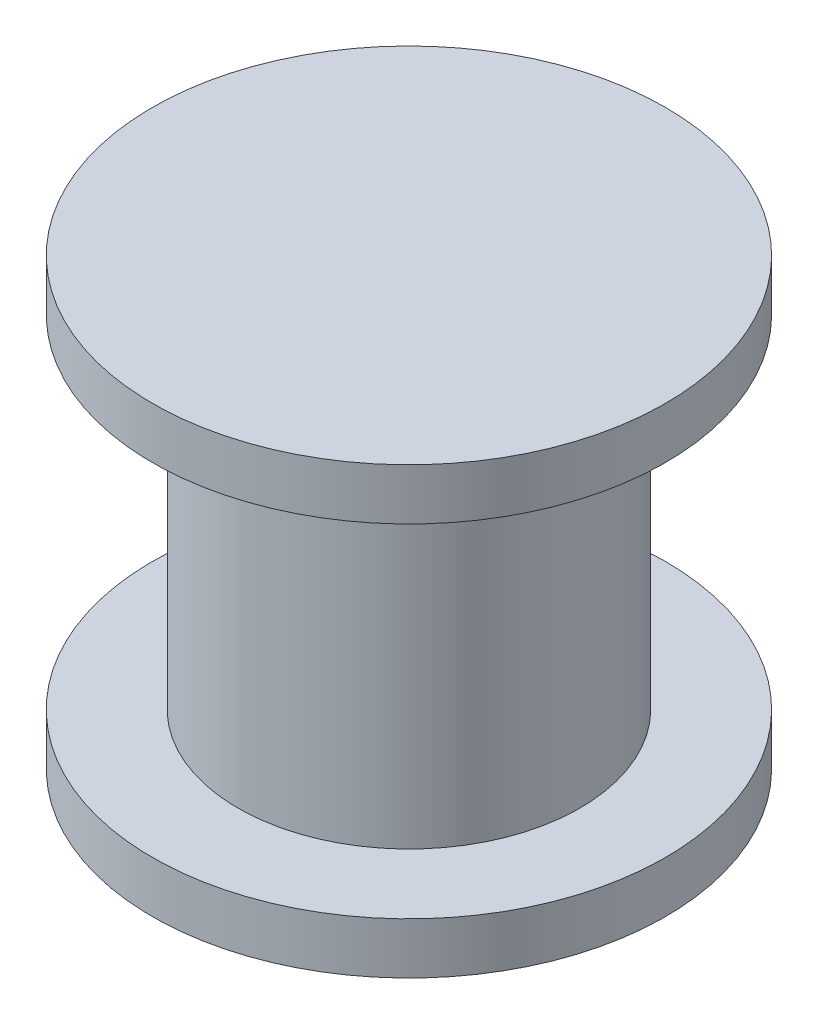
SolidWorks part; units mm, degrees
ref_plane "前基準面" through (0, 0, 0) normal (0, 0, 1) x (1, 0, 0)
ref_plane "上基準面" through (0, 0, 0) normal (0, 1, 0) x (1, 0, 0)
ref_plane "右基準面" through (0, 0, 0) normal (1, 0, 0) x (0, 0, -1)
sketch "草圖1" plane through (0, 0, 0) normal (0, 0, 1) x (1, 0, 0)
  line L0 (0, 0) -> (0, 64.884) construction
  line L2 (0, 0) -> (-15, 0)
  line L3 (0, 0) -> (0, 3)
  line L4 (0, 3) -> (-15, 3)
  line L5 (-15, 0) -> (-15, 3)
  line L6 (0, 3) -> (-10, 3)
  line L7 (0, 3) -> (0, 23)
  line L8 (0, 23) -> (-10, 23)
  line L9 (-10, 3) -> (-10, 23)
  line L10 (0, 23) -> (-15, 23)
  line L11 (0, 23) -> (0, 26)
  line L12 (0, 26) -> (-15, 26)
  line L13 (-15, 23) -> (-15, 26)
  dimension "D1" = 30
  dimension "D2" = 20
  dimension "D3" = 30
  dimension "D4" = 20
  dimension "D5" = 3
  dimension "D6" = 3
revolve "旋轉1" add sketch "草圖1" angle 360 about L0
